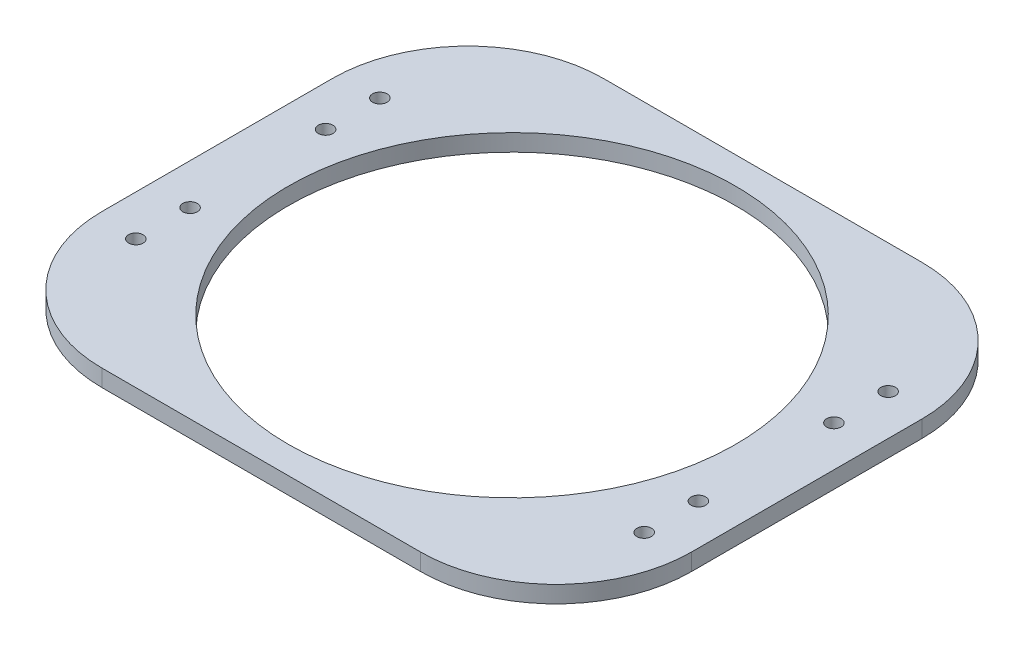
SolidWorks part; units mm, degrees
ref_plane "Front Plane" through (0, 0, 0) normal (0, 0, 1) x (1, 0, 0)
ref_plane "Top Plane" through (0, 0, 0) normal (0, 1, 0) x (1, 0, 0)
ref_plane "Right Plane" through (0, 0, 0) normal (1, 0, 0) x (0, 0, -1)
sketch "Sketch1" plane through (0, 0, 0) normal (0, 1, 0) x (1, 0, 0)
  line L0 (66, 74) -> (66, -74) construction
  line L5 (87, -74) -> (-87, -74)
  line L6 (87, -74) -> (87, 74)
  line L7 (87, 74) -> (-87, 74)
  line L8 (-87, -74) -> (-87, 74)
  line L9 (87, -74) -> (-87, 74) construction
  line L10 (87, 74) -> (-87, -74) construction
  line L11 (75, 74) -> (75, -74) construction
  line L12 (87, 0) -> (-87, 0) construction
  line L13 (0, 74) -> (0, -74) construction
  circle A0 centre (0, 0) radius 66
  circle A1 centre (75, 36) radius 2.15
  circle A2 centre (75, 20) radius 2.15
  circle A3 centre (75, -20) radius 2.15
  circle A4 centre (75, -36) radius 2.15
  circle A5 centre (-75, -36) radius 2.15
  circle A6 centre (-75, -20) radius 2.15
  circle A7 centre (-75, 20) radius 2.15
  circle A8 centre (-75, 36) radius 2.15
  dimension "D1" = 132
  dimension "D3" = 16
  dimension "D4" = 4.3
  dimension "D5" = 40
  dimension "D7" = 74
  dimension "D2" = 9
  dimension "D6" = 12
extrude "Boss-Extrude1" add sketch "Sketch1" along normal blind 5
fillet "Fillet1" radius 40 4 edges at (-87, 2.5, -74) (87, 2.5, -74) (87, 2.5, 74) (-87, 2.5, 74)
